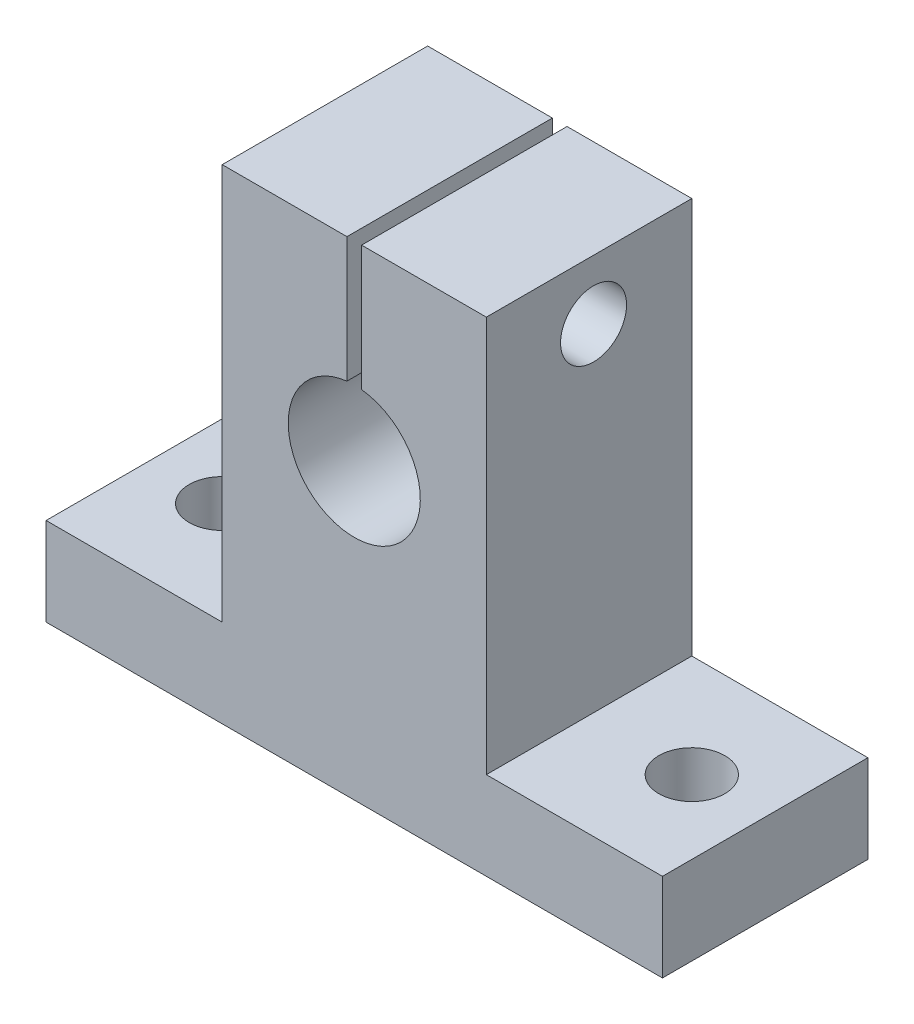
SolidWorks part; units mm, degrees
material "Alumina"
ref_plane "Front Plane" through (0, 0, 0) normal (0, 0, 1) x (1, 0, 0)
ref_plane "Top Plane" through (0, 0, 0) normal (0, 1, 0) x (1, 0, 0)
ref_plane "Right Plane" through (0, 0, 0) normal (1, 0, 0) x (0, 0, -1)
sketch "Sketch1" plane through (0, 0, 0) normal (0, 0, 1) x (1, 0, 0)
  line L0 (21, 3) -> (-21, -3) construction
  line L1 (-21, -3) -> (21, -3)
  line L2 (-21, -3) -> (-21, 3)
  line L3 (-21, 3) -> (21, 3)
  line L4 (21, -3) -> (21, 3)
  line L5 (-21, 3) -> (21, -3) construction
  line L7 (-9, 3) -> (9, 3)
  line L8 (-9, 3) -> (-9, 30)
  line L9 (-9, 30) -> (9, 30)
  line L10 (9, 3) -> (9, 30)
  circle A0 centre (0, 17) radius 4.5
  point P4 (0, 0)
  point P10 (0, 30)
  point P11 (0, 3)
  dimension "D5" = 13
  dimension "D6" = 9
  dimension "D1" = 42
  dimension "D2" = 6
  dimension "D3" = 18
  dimension "D4" = 27
extrude "Boss-Extrude1" add sketch "Sketch1" along normal blind 14 contours L3 L10 L9 L8 A0 | L1 L4 L3 L2
sketch "Sketch2" plane through (0, 3, 0) normal (0, 1, 0) x (1, 0, 0)
  line L0 (-21, -14) -> (-21, 0) construction
  line L3 (-21, 0) -> (-9, 0) construction
  line L6 (0, 0) -> (0, -14) construction
  line L7 (-9, -14) -> (9, -14) construction
  circle A0 centre (-16, -7) radius 2.25
  circle A1 centre (16, -7) radius 2.25
  dimension "D1" = 4.5
  dimension "D2" = 5
  dimension "D3" = 7
extrude "Cut-Extrude1" cut sketch "Sketch2" against normal through all
sketch "Sketch3" plane through (0, 0, 14) normal (0, 0, 1) x (1, 0, 0)
  line L0 (0, 30) -> (0, -3) construction
  line L1 (-9, 30) -> (9, 30) construction
  line L2 (-21, -3) -> (21, -3) construction
  line L3 (0.5, 30) -> (0.5, 21.4721)
  line L4 (-0.5, 30) -> (-0.5, 21.4721)
  line L5 (-0.5, 30) -> (0.5, 30)
  circle A0 centre (0, 17) radius 4.5 construction
  arc A1 (-0.5, 21.4721) -> (0.5, 21.4721) centre (0, 17) cw
  dimension "D1" = 0.5
extrude "Cut-Extrude2" cut sketch "Sketch3" against normal through all
sketch "Sketch4" plane through (9, 0, 0) normal (1, 0, 0) x (0, 0, -1)
  line L0 (-14, 30) -> (0, 30) construction
  circle A0 centre (-6.6953, 25.95) radius 2.25
  dimension "D1" = 4.5
  dimension "D2" = 4.05
extrude "Cut-Extrude3" cut sketch "Sketch4" against normal up to surface (18 mm away) up to face at (-9, 16.5, 7)
